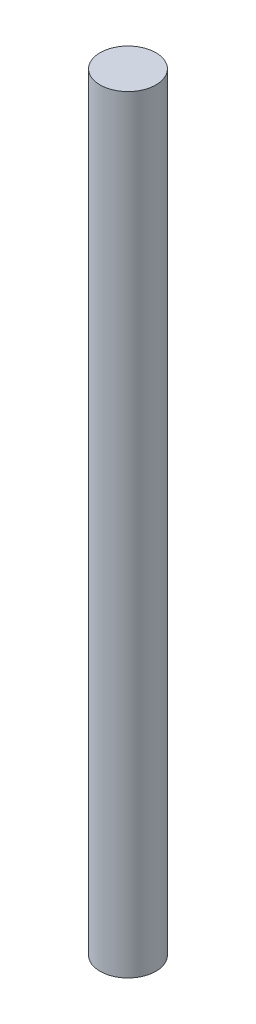
SolidWorks part; units mm, degrees
ref_plane "前视基准面" through (0, 0, 0) normal (0, 0, 1) x (1, 0, 0)
ref_plane "上视基准面" through (0, 0, 0) normal (0, 1, 0) x (1, 0, 0)
ref_plane "右视基准面" through (0, 0, 0) normal (1, 0, 0) x (0, 0, -1)
sketch "草图1" plane through (0, 0, 0) normal (0, 1, 0) x (1, 0, 0)
  circle A0 centre (0, 0) radius 4
extrude "凸台-拉伸1" add sketch "草图1" along normal blind 110
